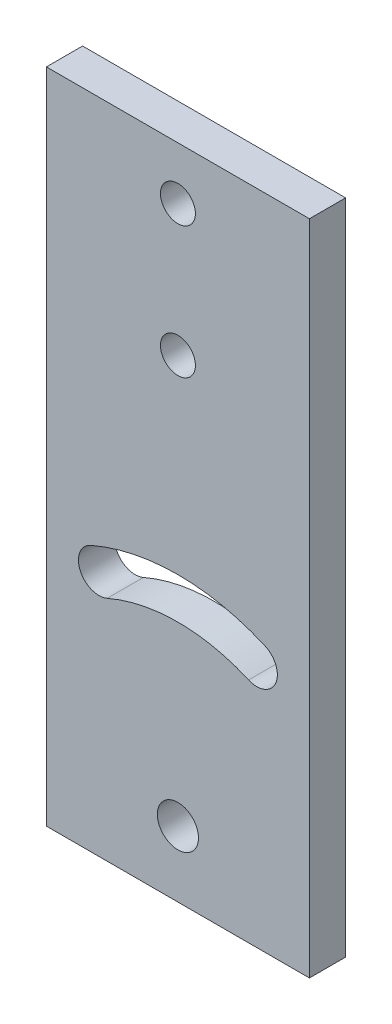
SolidWorks part; units mm, degrees
ref_plane "Front Plane" through (0, 0, 0) normal (0, 0, 1) x (1, 0, 0)
ref_plane "Top Plane" through (0, 0, 0) normal (0, 1, 0) x (1, 0, 0)
ref_plane "Right Plane" through (0, 0, 0) normal (1, 0, 0) x (0, 0, -1)
sketch "Sketch1" plane through (0, 0, 0) normal (0, 0, 1) x (1, 0, 0)
  line L1 (0, 0) -> (50.8, 0)
  line L2 (0, 0) -> (0, 127)
  line L3 (0, 127) -> (50.8, 127)
  line L4 (50.8, 0) -> (50.8, 127)
  circle A0 centre (25.4, 12.7) radius 3.9687
  circle A6 centre (25.4, 116.84) radius 3.3734
  circle A7 centre (25.4, 91.44) radius 3.3734
  arc A8 (42.2275, 51.2566) -> (8.5725, 51.2566) centre (25.4, 12.7) ccw
  arc A9 (39.0525, 43.9818) -> (11.7475, 43.9818) centre (25.4, 12.7) ccw
  arc A10 (8.5725, 51.2566) -> (11.7475, 43.9818) centre (10.16, 47.6192) ccw
  arc A11 (39.0525, 43.9818) -> (42.2275, 51.2566) centre (40.64, 47.6192) ccw
  arc A12 (43.7515, 54.7486) -> (7.0485, 54.7486) centre (25.4, 12.7) ccw
  arc A13 (7.0485, 54.7486) -> (13.2715, 40.4899) centre (10.16, 47.6192) ccw
  arc A14 (37.5285, 40.4899) -> (13.2715, 40.4899) centre (25.4, 12.7) ccw
  arc A15 (37.5285, 40.4899) -> (43.7515, 54.7486) centre (40.64, 47.6192) ccw
  dimension "D3" = 7.9375
  dimension "D6" = 6.7469
  dimension "D7" = 7.9375
  dimension "D8" = 7.9375
  dimension "D9" = 6.7469
  dimension "D13" = 84.1375
  dimension "D14" = 68.2625
  dimension "D1" = 127
  dimension "D2" = 50.8
  dimension "D4" = 25.4
  dimension "D5" = 12.7
  dimension "D10" = 10.16
  dimension "D11" = 10.16
  dimension "D12" = 25.4
  dimension "D15" = 10.16
  dimension "D17" = 25.4
  dimension "D18" = 0
  dimension "D16" = 3.81
extrude "Boss-Extrude2" add sketch "Sketch1" along normal blind 6.985 contours L2 L1 L4 L3 | A11 A8 A10 A9 | A7 | A6 | A0
